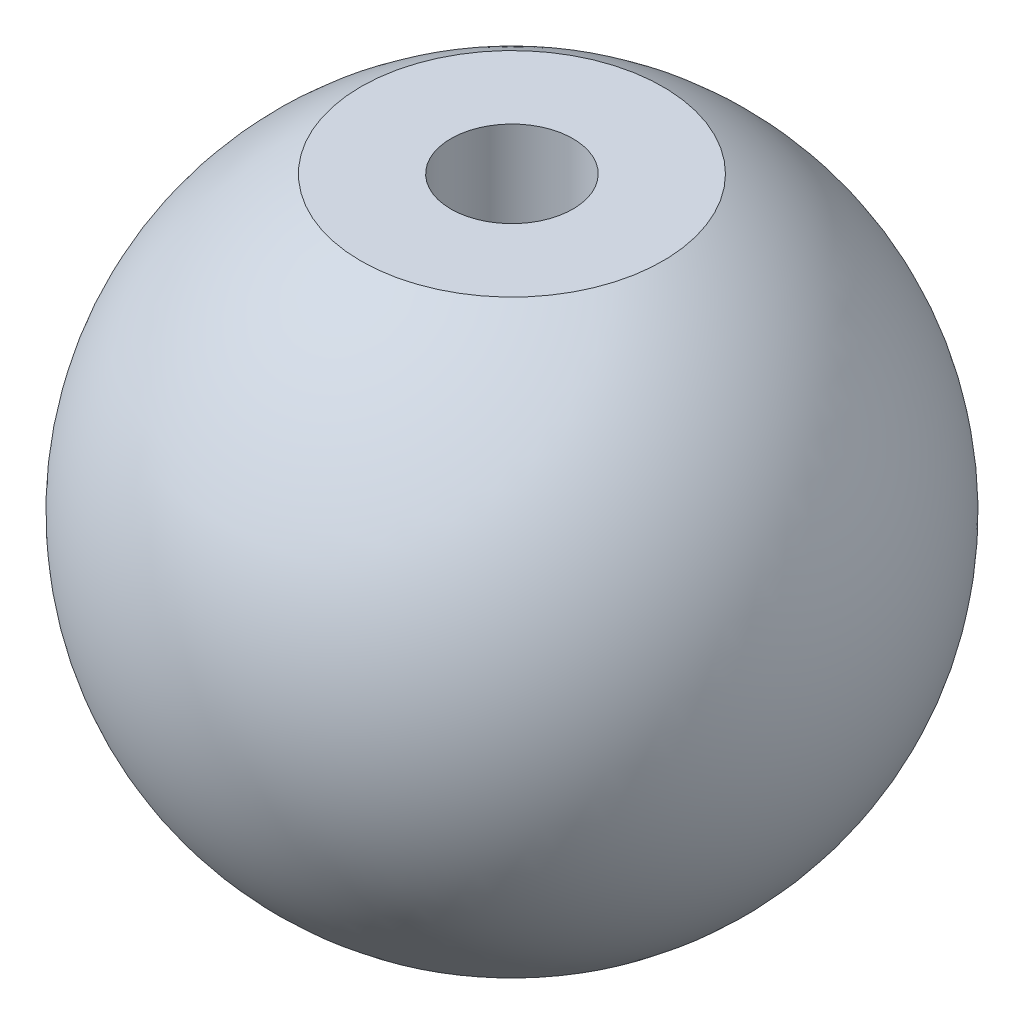
SolidWorks part; units mm, degrees
material "SKD11淬火HRC56-60"
ref_plane "前基準面" through (0, 0, 0) normal (0, 0, 1) x (1, 0, 0)
ref_plane "上基準面" through (0, 0, 0) normal (0, 1, 0) x (1, 0, 0)
ref_plane "右基準面" through (0, 0, 0) normal (1, 0, 0) x (0, 0, -1)
sketch "草图1" plane through (0, 0, 0) normal (0, 0, 1) x (1, 0, 0)
  line L0 (0, 0) -> (0, 19.4799) construction
  line L1 (0, 13.5) -> (0, -13.5)
  arc A0 (0, -13.5) -> (0, 13.5) centre (0, 0) ccw
  dimension "D1" = 27
revolve "旋转1" add sketch "草图1" angle 360 about L0
ref_plane "基准面1" through (0, 12, 0) normal (0, 1, 0) x (-1, 0, 0)
sketch "草图2" plane through (0, 12, 0) normal (0, 1, 0) x (-1, 0, 0)
  circle A0 centre (0, 0) radius 15.9387
extrude "切除-拉伸1" cut sketch "草图2" along normal blind 10
hole_wizard "M6 螺纹孔1" positions "草图4" profile "草图3" tap size "M6" standard "ISO"
sketch "草图4" plane through (0, 12, 0) normal (0, 1, 0) x (-1, 0, 0)
  point P0 (0, 0)
sketch "草图3" plane through (0, 12, 0) normal (1, 0, 0) x (0, 0, 1)
  line L0 (0, 0) -> (0, 16.5022)
  line L1 (0, 16.5022) -> (2.5, 15)
  line L2 (2.5, 15) -> (2.5, 0)
  line L5 (2.5, 0) -> (0, 0)
  line L10 (0, 16.5022) -> (-2.5, 15) construction
  line L11 (0, -6.35) -> (0, 107.95) construction
  dimension "螺纹孔钻头直径" = 5
  dimension "螺纹孔钻头深度" = 15
  dimension "导头角度" = 118
cosmetic thread "孔螺蚊线1" parameters "D1"=12, "D2"=6
